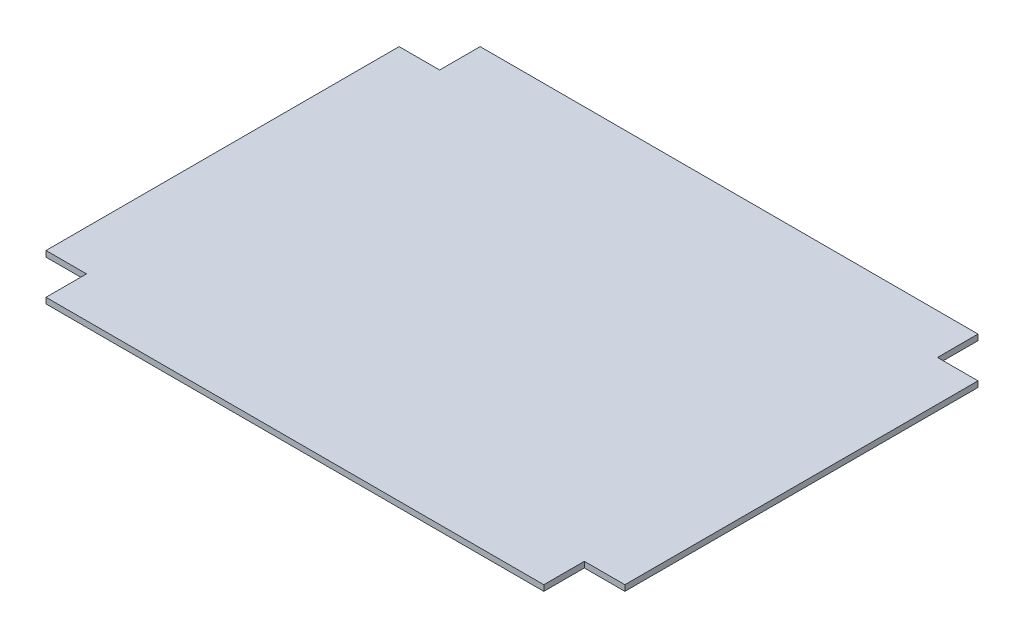
SolidWorks part; units mm, degrees
ref_plane "Front" through (0, 0, 0) normal (0, 0, 1) x (1, 0, 0)
ref_plane "Top" through (0, 0, 0) normal (0, 1, 0) x (1, 0, 0)
ref_plane "Right" through (0, 0, 0) normal (1, 0, 0) x (0, 0, -1)
sketch "Эскиз1" plane through (0, 0, 0) normal (0, 1, 0) x (1, 0, 0)
  line L0 (-1446.0698, -220.6238) -> (-1446.0698, -262.6238)
  line L1 (-930.0698, -220.6238) -> (-1446.0698, -220.6238)
  line L2 (-888.0698, -262.6238) -> (-888.0698, -628.6238)
  line L3 (-930.0698, -670.6238) -> (-1446.0698, -670.6238)
  line L4 (-1488.0698, -262.6238) -> (-1488.0698, -628.6238)
  line L5 (-1446.0698, -262.6238) -> (-1488.0698, -262.6238)
  line L6 (-930.0698, -220.6238) -> (-930.0698, -262.6238)
  line L7 (-930.0698, -262.6238) -> (-888.0698, -262.6238)
  line L8 (-888.0698, -628.6238) -> (-930.0698, -628.6238)
  line L9 (-930.0698, -628.6238) -> (-930.0698, -670.6238)
  line L10 (-1488.0698, -628.6238) -> (-1446.0698, -628.6238)
  line L11 (-1446.0698, -628.6238) -> (-1446.0698, -670.6238)
  point P15 (-1467.0698, -262.6238)
  dimension "D1" = 450
  dimension "D2" = 600
  dimension "D3" = 42
  dimension "D4" = 42
  dimension "D5" = 42
  dimension "D6" = 42
extrude "Бобышка-Вытянуть1" add sketch "Эскиз1" along normal blind 6
ref_plane "Плоскость1" through (-1188.0698, 0, 0) normal (1, 0, 0) x (0, 0, -1)
